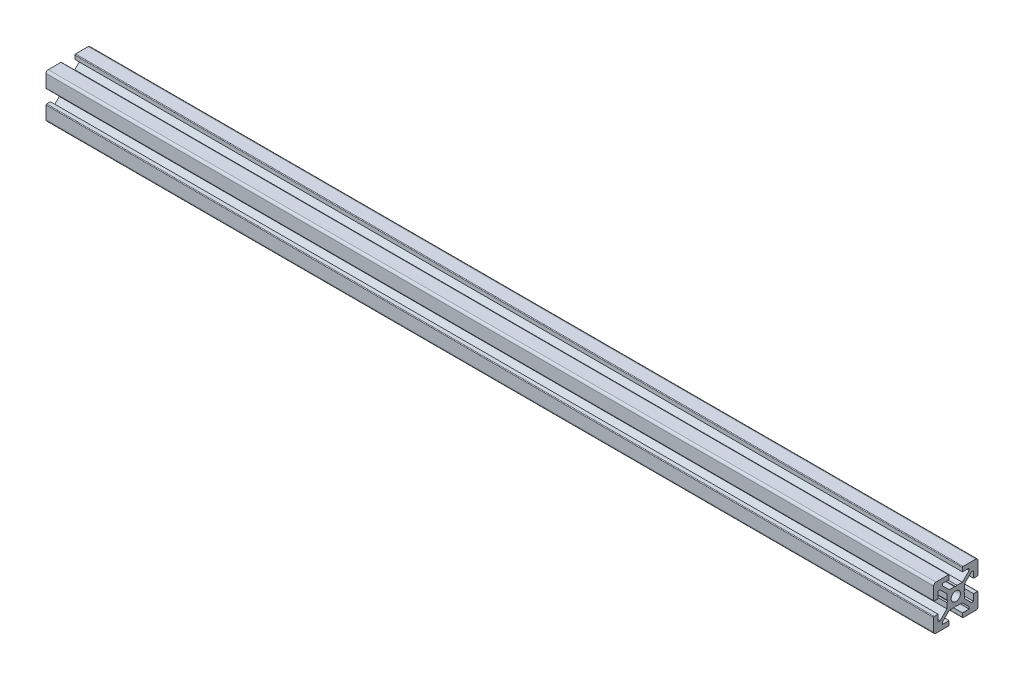
SolidWorks part; units mm, degrees
ref_plane "Front Plane" through (0, 0, 0) normal (0, 0, 1) x (1, 0, 0)
ref_plane "Top Plane" through (0, 0, 0) normal (0, 1, 0) x (1, 0, 0)
ref_plane "Right Plane" through (0, 0, 0) normal (1, 0, 0) x (0, 0, -1)
sketch "Sketch1" plane through (0, 0, 0) normal (1, 0, 0) x (0, 0, -1)
  line L0 (-9.9351, 3.3809) -> (-9.9351, 9.0809)
  line L1 (-8.9351, 10.0809) -> (-3.2351, 10.0809)
  line L2 (-2.9351, 9.7809) -> (-2.9351, 8.0809)
  line L3 (-2.9351, 8.0809) -> (-5.9351, 8.0809)
  line L4 (-5.9351, 8.0809) -> (-5.9351, 7.1416)
  line L5 (-5.9351, 7.1416) -> (-2.8744, 4.0809)
  line L6 (-2.8744, 4.0809) -> (-0.4547, 4.0809)
  line L7 (-0.4547, 4.0809) -> (0.0649, 3.7809)
  line L8 (0.0649, 3.7809) -> (0.5845, 4.0809)
  line L9 (0.5845, 4.0809) -> (3.0043, 4.0809)
  line L10 (3.0043, 4.0809) -> (6.0649, 7.1416)
  line L11 (6.0649, 7.1416) -> (6.0649, 8.0809)
  line L12 (6.0649, 8.0809) -> (3.0649, 8.0809)
  line L13 (3.0649, 8.0809) -> (3.0649, 9.7809)
  line L14 (3.3649, 10.0809) -> (9.0649, 10.0809)
  line L15 (10.0649, 9.0809) -> (10.0649, 3.3809)
  line L16 (9.7649, 3.0809) -> (8.0649, 3.0809)
  line L17 (8.0649, 3.0809) -> (8.0649, 6.0809)
  line L18 (8.0649, 6.0809) -> (7.1256, 6.0809)
  line L19 (7.1256, 6.0809) -> (4.0649, 3.0203)
  line L20 (4.0649, 3.0203) -> (4.0649, 0.6005)
  line L21 (4.0649, 0.6005) -> (3.7649, 0.0809)
  line L22 (3.7649, 0.0809) -> (4.0649, -0.4387)
  line L23 (4.0649, -0.4387) -> (4.0649, -2.8584)
  line L24 (4.0649, -2.8584) -> (7.1256, -5.9191)
  line L25 (7.1256, -5.9191) -> (8.0649, -5.9191)
  line L26 (8.0649, -5.9191) -> (8.0649, -2.9191)
  line L27 (8.0649, -2.9191) -> (9.7649, -2.9191)
  line L28 (10.0649, -3.2191) -> (10.0649, -8.9191)
  line L29 (9.0649, -9.9191) -> (3.3649, -9.9191)
  line L30 (3.0649, -9.6191) -> (3.0649, -7.919)
  line L31 (3.0649, -7.919) -> (6.0649, -7.919)
  line L32 (6.0649, -7.919) -> (6.0649, -6.9797)
  line L33 (6.0649, -6.9797) -> (3.0043, -3.9191)
  line L34 (3.0043, -3.9191) -> (0.5845, -3.9191)
  line L35 (0.5845, -3.9191) -> (0.0649, -3.6191)
  line L36 (0.0649, -3.6191) -> (-0.4547, -3.9191)
  line L37 (-0.4547, -3.9191) -> (-2.8744, -3.9191)
  line L38 (-2.8744, -3.9191) -> (-5.9351, -6.9797)
  line L39 (-5.9351, -6.9797) -> (-5.9351, -7.919)
  line L40 (-5.9351, -7.919) -> (-2.9351, -7.919)
  line L41 (-2.9351, -7.919) -> (-2.9351, -9.6191)
  line L42 (-3.2351, -9.9191) -> (-8.9351, -9.9191)
  line L43 (-9.9351, -8.9191) -> (-9.9351, -3.2191)
  line L44 (-9.6351, -2.9191) -> (-7.9351, -2.9191)
  line L45 (-7.9351, -2.9191) -> (-7.9351, -5.9191)
  line L46 (-7.9351, -5.9191) -> (-6.9958, -5.9191)
  line L47 (-6.9958, -5.9191) -> (-3.9351, -2.8584)
  line L48 (-3.9351, -2.8584) -> (-3.9351, -0.4387)
  line L49 (-3.9351, -0.4387) -> (-3.6351, 0.0809)
  line L50 (-3.6351, 0.0809) -> (-3.9351, 0.6005)
  line L51 (-3.9351, 0.6005) -> (-3.9351, 3.0203)
  line L52 (-3.9351, 3.0203) -> (-6.9958, 6.0809)
  line L53 (-6.9958, 6.0809) -> (-7.9351, 6.0809)
  line L54 (-7.9351, 6.0809) -> (-7.9351, 3.0809)
  line L55 (-7.9351, 3.0809) -> (-9.6351, 3.0809)
  arc A0 (-9.9351, 9.0809) -> (-8.9351, 10.0809) centre (-8.9351, 9.0809) cw
  arc A1 (-3.2351, 10.0809) -> (-2.9351, 9.7809) centre (-3.2351, 9.7809) cw
  arc A2 (3.0649, 9.7809) -> (3.3649, 10.0809) centre (3.3649, 9.7809) cw
  arc A3 (9.0649, 10.0809) -> (10.0649, 9.0809) centre (9.0649, 9.0809) cw
  arc A4 (10.0649, 3.3809) -> (9.7649, 3.0809) centre (9.7649, 3.3809) cw
  arc A5 (9.7649, -2.9191) -> (10.0649, -3.2191) centre (9.7649, -3.2191) cw
  arc A6 (10.0649, -8.9191) -> (9.0649, -9.9191) centre (9.0649, -8.9191) cw
  arc A7 (3.0649, -9.6191) -> (3.3649, -9.9191) centre (3.3649, -9.6191) ccw
  arc A8 (-2.9351, -9.6191) -> (-3.2351, -9.9191) centre (-3.2351, -9.6191) cw
  arc A9 (-9.9351, -8.9191) -> (-8.9351, -9.9191) centre (-8.9351, -8.9191) ccw
  arc A10 (-9.6351, -2.9191) -> (-9.9351, -3.2191) centre (-9.6351, -3.2191) ccw
  arc A11 (-9.9351, 3.3809) -> (-9.6351, 3.0809) centre (-9.6351, 3.3809) ccw
  circle A12 centre (0.0649, 0.0809) radius 2.1
extrude "Boss-Extrude1" add sketch "Sketch1" along normal blind 400
